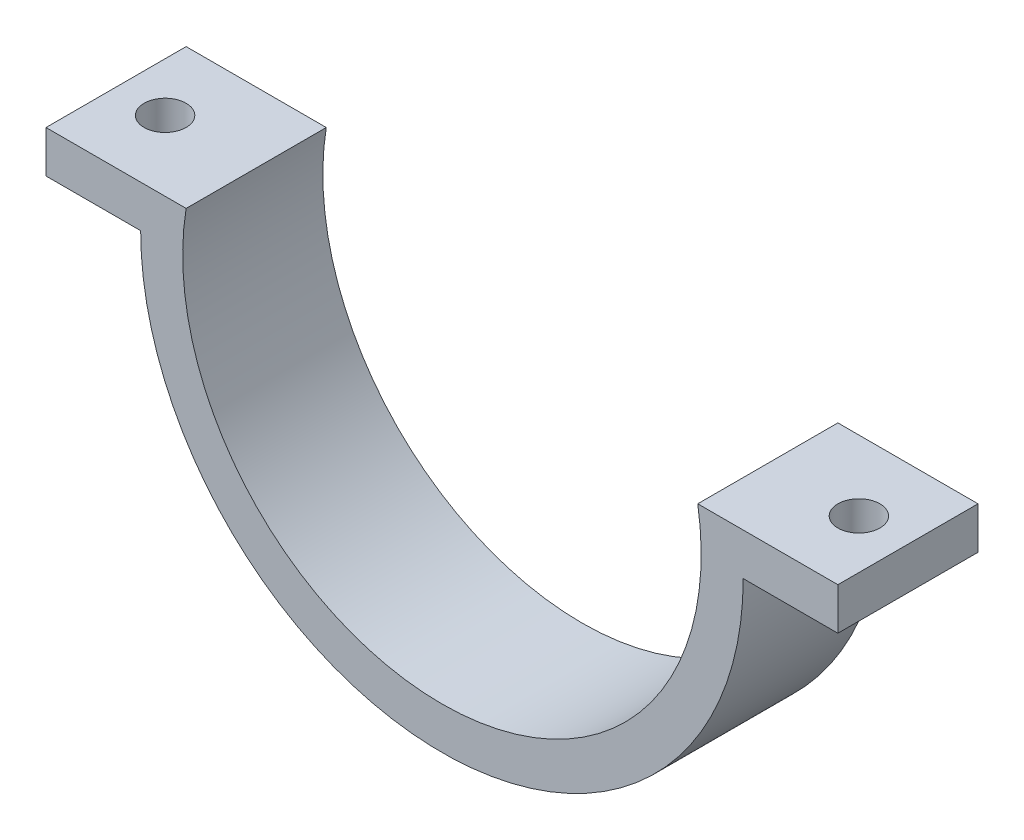
SolidWorks part; units mm, degrees
ref_plane "Front Plane" through (0, 0, 0) normal (0, 0, 1) x (1, 0, 0)
ref_plane "Top Plane" through (0, 0, 0) normal (0, 1, 0) x (1, 0, 0)
ref_plane "Right Plane" through (0, 0, 0) normal (1, 0, 0) x (0, 0, -1)
sketch "Sketch1" plane through (0, 0, 0) normal (0, 0, 1) x (1, 0, 0)
  line L0 (0, 0) -> (0, 3) construction
  line L1 (18.2551, 3) -> (-18.2551, 3) construction
  line L2 (-18.2551, 3) -> (-28.2551, 3)
  line L3 (18.2551, 3) -> (28.2551, 3)
  line L4 (-28.2551, 3) -> (-28.2551, 0)
  line L5 (-28.2551, 0) -> (-21.5, 0)
  line L6 (28.2551, 0) -> (21.5, 0)
  line L7 (28.2551, 3) -> (28.2551, 0)
  circle A0 centre (0, 0) radius 18.5
  arc A1 (-21.5, 0) -> (21.5, 0) centre (0, 0) ccw
  dimension "D1" = 37
  dimension "D4" = 3
  dimension "D2" = 3
  dimension "D3" = 10
  dimension "D5" = 3
extrude "Boss-Extrude1" add sketch "Sketch1" along normal blind 10 contours L5 A1 L6 L7 L3 A0 L2 L4
sketch "Sketch2" plane through (0, 3, 0) normal (0, 1, 0) x (1, 0, 0)
  line L0 (-28.2551, -5) -> (-26.2551, -5)
  line L1 (-28.2551, -10) -> (-28.2551, 0) construction
  line L2 (-26.2551, -5) -> (-18.2551, -5)
  line L3 (-18.2551, -10) -> (-18.2551, 0) construction
  circle A0 centre (-24.7551, -5) radius 1.5
  point P9 (-23.2551, -5)
  dimension "D2" = 3
  dimension "D1" = 2
extrude "Cut-Extrude1" cut sketch "Sketch2" against normal up to surface (3 mm away) contours L2 A0 | L2 A0 up to face at (-24.8776, 0, 5)
mirror "Mirror1" about plane through (0, 0, 0) normal (1, 0, 0) of "Cut-Extrude1"
